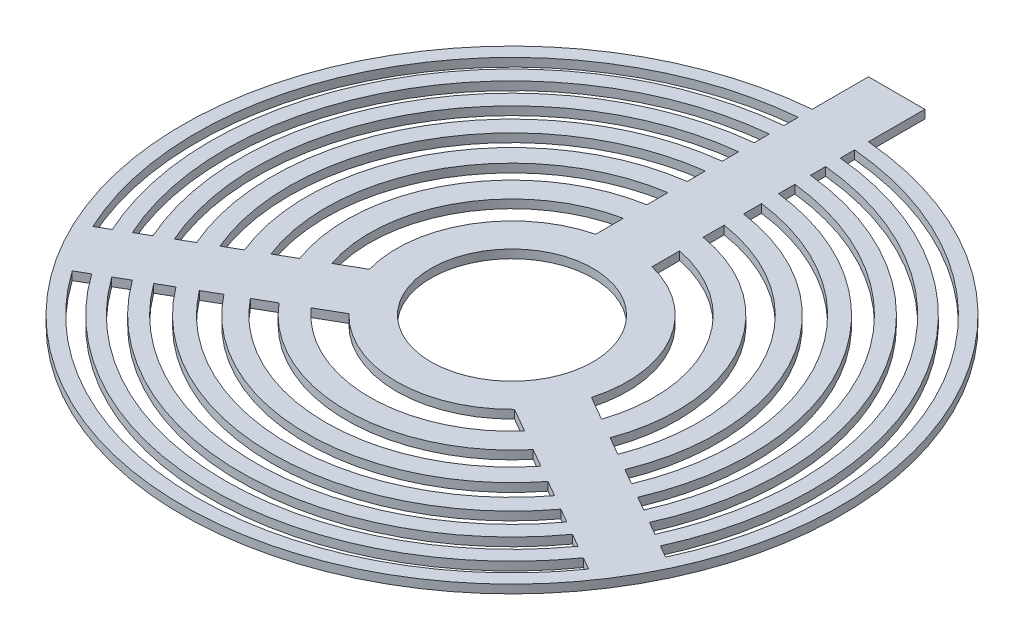
SolidWorks part; units mm, degrees
ref_plane "前视基准面" through (0, 0, 0) normal (0, 0, 1) x (1, 0, 0)
ref_plane "上视基准面" through (0, 0, 0) normal (0, 1, 0) x (1, 0, 0)
ref_plane "右视基准面" through (0, 0, 0) normal (1, 0, 0) x (0, 0, -1)
other "Configuration Table"
sketch "草图4" plane through (0, 0, 0) normal (0, 1, 0) x (1, 0, 0)
  line L0 (0, 25.4837) -> (0, 26.9762) construction
  line L13 (-101.677, -47.1562) -> (-97.2939, -44.6257)
  line L14 (-92.7872, -42.0237) -> (-88.1389, -39.34)
  line L15 (-83.331, -36.5642) -> (-78.319, -33.6705)
  line L16 (-73.0752, -30.643) -> (-67.5277, -27.4401)
  line L17 (-61.5854, -24.0093) -> (-55.119, -20.2759)
  line L18 (-47.8859, -16.0999) -> (-39.4079, -11.2052)
  line L19 (-37.8859, -33.4205) -> (-29.4079, -28.5257)
  line L20 (-51.5854, -41.3298) -> (-45.119, -37.5964)
  line L21 (-63.0752, -47.9635) -> (-57.5277, -44.7606)
  line L22 (-82.7872, -59.3442) -> (-78.1389, -56.6605)
  line L23 (-73.331, -53.8847) -> (-68.319, -50.991)
  line L24 (-91.677, -64.4768) -> (-87.2939, -61.9462)
  line L25 (-10, 49.5204) -> (-10, 39.7309)
  line L26 (10, 49.5204) -> (10, 39.7309)
  line L27 (10, 65.3392) -> (10, 57.8724)
  line L28 (10, 78.6065) -> (10, 72.2008)
  line L29 (-10, 78.6065) -> (-10, 72.2008)
  line L30 (-10, 65.3392) -> (-10, 57.8724)
  line L31 (-10, 90.4489) -> (-10, 84.6615)
  line L32 (10, 90.4489) -> (10, 84.6615)
  line L33 (-10, 101.3679) -> (-10, 96.0006)
  line L34 (10, 101.3679) -> (10, 96.0006)
  line L35 (-10, 111.633) -> (-10, 106.5719)
  line L36 (10, 111.633) -> (10, 106.5719)
  line L41 (47.8859, -16.0999) -> (39.4079, -11.2052)
  line L42 (37.8859, -33.4205) -> (29.4079, -28.5257)
  line L43 (61.5854, -24.0093) -> (55.119, -20.2759)
  line L44 (51.5854, -41.3298) -> (45.119, -37.5964)
  line L45 (73.0752, -30.643) -> (67.5277, -27.4401)
  line L46 (63.0752, -47.9635) -> (57.5277, -44.7606)
  line L47 (83.331, -36.5642) -> (78.319, -33.6705)
  line L48 (73.331, -53.8847) -> (68.319, -50.991)
  line L49 (92.7872, -42.0237) -> (88.1389, -39.34)
  line L50 (82.7872, -59.3442) -> (78.1389, -56.6605)
  line L51 (101.677, -47.1562) -> (97.2939, -44.6257)
  line L52 (91.677, -64.4768) -> (87.2939, -61.9462)
  line L57 (-10, 116.5719) -> (-10, 136.5719)
  line L58 (-10, 136.5719) -> (10, 136.5719)
  line L59 (10, 136.5719) -> (10, 116.5719)
  circle A0 centre (0, 0) radius 28.77
  arc A1 (-10, 39.7309) -> (-39.4079, -11.2052) centre (0, 0) ccw
  arc A2 (-10, 49.5204) -> (-47.8859, -16.0999) centre (0, 0) ccw
  arc A3 (-10, 57.8724) -> (-55.119, -20.2759) centre (0, 0) ccw
  arc A4 (-10, 65.3392) -> (-61.5854, -24.0093) centre (0, 0) ccw
  arc A5 (-10, 72.2008) -> (-67.5277, -27.4401) centre (0, 0) ccw
  arc A6 (-10, 84.6615) -> (-78.319, -33.6705) centre (0, 0) ccw
  arc A7 (-10, 90.4489) -> (-83.331, -36.5642) centre (0, 0) ccw
  arc A8 (-10, 96.0006) -> (-88.1389, -39.34) centre (0, 0) ccw
  arc A9 (-10, 78.6065) -> (-73.0752, -30.643) centre (0, 0) ccw
  arc A10 (-10, 101.3679) -> (-92.7872, -42.0237) centre (0, 0) ccw
  arc A11 (-10, 106.5719) -> (-97.2939, -44.6257) centre (0, 0) ccw
  arc A12 (102.0755, -46.2874) -> (10, 111.633) centre (0, 0) ccw
  arc A13 (-10, 111.633) -> (-101.677, -47.1562) centre (0, 0) ccw
  arc A14 (-10, 116.5719) -> (-105.9542, -49.6257) centre (0, 0) ccw
  arc A21 (39.4079, -11.2052) -> (10, 39.7309) centre (0, 0) ccw
  arc A22 (47.8859, -16.0999) -> (10, 49.5204) centre (0, 0) ccw
  arc A23 (55.119, -20.2759) -> (10, 57.8724) centre (0, 0) ccw
  arc A24 (61.5854, -24.0093) -> (10, 65.3392) centre (0, 0) ccw
  arc A25 (67.5277, -27.4401) -> (10, 72.2008) centre (0, 0) ccw
  arc A26 (73.0752, -30.643) -> (10, 78.6065) centre (0, 0) ccw
  arc A27 (78.319, -33.6705) -> (10, 84.6615) centre (0, 0) ccw
  arc A28 (83.331, -36.5642) -> (10, 90.4489) centre (0, 0) ccw
  arc A29 (88.1389, -39.34) -> (10, 96.0006) centre (0, 0) ccw
  arc A30 (92.7872, -42.0237) -> (10, 101.3679) centre (0, 0) ccw
  arc A31 (97.2939, -44.6257) -> (10, 106.5719) centre (0, 0) ccw
  arc A32 (101.677, -47.1562) -> (10, 111.633) centre (0, 0) ccw
  arc A33 (101.677, -47.1562) -> (10, 111.633) centre (0, 0) ccw
  arc A34 (105.9542, -49.6257) -> (10, 116.5719) centre (0, 0) ccw
  arc A40 (-29.4079, -28.5257) -> (29.4079, -28.5257) centre (0, 0) ccw
  arc A41 (-37.8859, -33.4205) -> (37.8859, -33.4205) centre (0, 0) ccw
  arc A42 (-45.119, -37.5964) -> (45.119, -37.5964) centre (0, 0) ccw
  arc A43 (-51.5854, -41.3298) -> (51.5854, -41.3298) centre (0, 0) ccw
  arc A44 (-57.5277, -44.7606) -> (57.5277, -44.7606) centre (0, 0) ccw
  arc A45 (-63.0752, -47.9635) -> (63.0752, -47.9635) centre (0, 0) ccw
  arc A46 (-68.319, -50.991) -> (68.319, -50.991) centre (0, 0) ccw
  arc A47 (-73.331, -53.8847) -> (73.331, -53.8847) centre (0, 0) ccw
  arc A48 (-78.1389, -56.6605) -> (78.1389, -56.6605) centre (0, 0) ccw
  arc A49 (-82.7872, -59.3442) -> (82.7872, -59.3442) centre (0, 0) ccw
  arc A50 (-87.2939, -61.9462) -> (87.2939, -61.9462) centre (0, 0) ccw
  arc A51 (-91.677, -64.4768) -> (91.677, -64.4768) centre (0, 0) ccw
  arc A52 (-91.677, -64.4768) -> (91.677, -64.4768) centre (0, 0) ccw
  arc A53 (-95.9542, -66.9462) -> (95.9542, -66.9462) centre (0, 0) ccw
  arc A59 (-10, 111.633) -> (-101.677, -47.1562) centre (0, 0) ccw
  arc A60 (-10, 116.5719) -> (10, 116.5719) centre (0, 0) ccw
  point P4 (0, 0)
  point P17 (0, 0)
  point P18 (-10.3036, 116.5454)
  point P40 (0, 0)
  dimension "D1" = 57.54
  dimension "D2" = 81.94
  dimension "D3" = 101.04
  dimension "D4" = 117.46
  dimension "D5" = 132.2
  dimension "D6" = 145.78
  dimension "D7" = 158.48
  dimension "D8" = 170.5
  dimension "D9" = 182
  dimension "D10" = 193.04
  dimension "D11" = 203.72
  dimension "D12" = 214.08
  dimension "D13" = 224.16
  dimension "D14" = 20
  dimension "D15" = 234
  dimension "D22" = 20
extrude "凸台-拉伸2" add sketch "草图4" along normal blind 3 contours A53 A60 A34 L59 L58 L57 A14 A0 A2 L25 A1 L18 A4 L30 A3 L17 A7 L31 A6 L15 A9 L29 A5 L16 A10 L33 A8 L14 A13 L35 A11 L13 A22 L41 A21 L26 A24 L43 A23 L27
